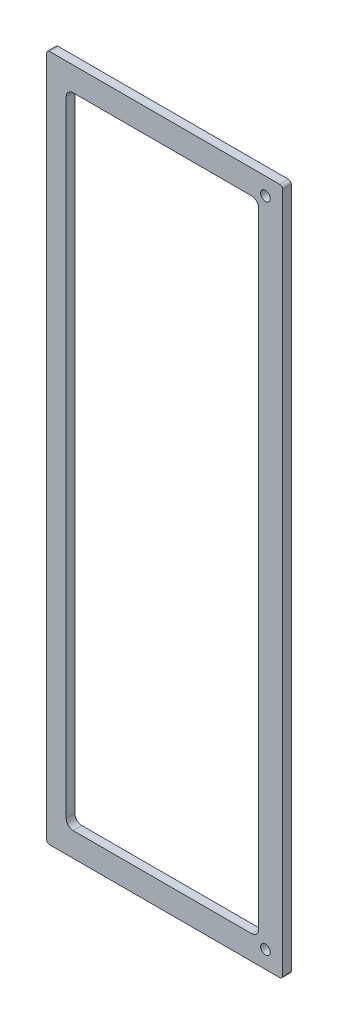
SolidWorks part; units mm, degrees
ref_plane "Front Plane" through (0, 0, 0) normal (1, 0, 0) x (0, 1, 0)
ref_plane "Top Plane" through (0, 0, 0) normal (0, 0, 1) x (0, 1, 0)
ref_plane "Right Plane" through (0, 0, 0) normal (0, 1, 0) x (-1, 0, 0)
sketch "Sketch1" plane through (0, 0, 0) normal (0, 0, 1) x (0, 1, 0)
  line L0 (12.5, 12.5) -> (12.5, 137.5)
  line L1 (-12.5, -12.5) -> (12.5, -12.5)
  line L2 (-12.5, -12.5) -> (-12.5, 12.5)
  line L3 (-12.5, 12.5) -> (12.5, 12.5)
  line L4 (12.5, -12.5) -> (12.5, 12.5)
  line L5 (-12.5, -12.5) -> (12.5, 12.5) construction
  line L6 (-12.5, 12.5) -> (12.5, -12.5) construction
  line L7 (-12.5, -12.5) -> (487.5, -12.5)
  line L8 (-12.5, -12.5) -> (-12.5, 162.5)
  line L9 (-12.5, 162.5) -> (487.5, 162.5)
  line L10 (487.5, -12.5) -> (487.5, 162.5)
  line L11 (-12.5, -12.5) -> (487.5, 162.5) construction
  line L12 (-12.5, 162.5) -> (487.5, -12.5) construction
  line L13 (487.5, -12.5) -> (462.5, -12.5)
  line L14 (487.5, -12.5) -> (487.5, 12.5)
  line L15 (487.5, 12.5) -> (462.5, 12.5)
  line L16 (462.5, -12.5) -> (462.5, 12.5)
  line L17 (487.5, -12.5) -> (462.5, 12.5) construction
  line L18 (487.5, 12.5) -> (462.5, -12.5) construction
  line L19 (-12.5, 162.5) -> (487.5, 162.5)
  line L20 (-12.5, 162.5) -> (-12.5, 137.5)
  line L21 (-12.5, 137.5) -> (487.5, 137.5)
  line L22 (487.5, 162.5) -> (487.5, 137.5)
  line L23 (-12.5, 162.5) -> (487.5, 137.5) construction
  line L24 (-12.5, 137.5) -> (487.5, 162.5) construction
  line L25 (12.5, 12.5) -> (462.5, 12.5)
  line L26 (462.5, 12.5) -> (462.5, 137.5)
  circle A0 centre (0, 0) radius 3.5
  circle A1 centre (475, 0) radius 3.5
  point P0 (0, 0)
  point P11 (237.5, 75)
  point P15 (475, 0)
  point P20 (237.5, 150)
  dimension "D2" = 7
  dimension "D6" = 7
  dimension "D1" = 25
  dimension "D3" = 500
  dimension "D4" = 175
  dimension "D5" = 25
  dimension "D7" = 25
extrude "Boss-Extrude1" add sketch "Sketch1" along normal blind 6.35 contours L8 L21 L10 L9 | L21 L8 L3 L0 | L25 L4 L7 L16 | L26 L15 L10 L21 | L16 L7 L10 L15 A1 | L1 L4 L3 L2 A0
sketch "Sketch2" plane through (0, 0, 6.35) normal (0, 0, 1) x (1, 0, 0)
  line L0 (-137.5, 12.5) -> (-12.5, 462.5) construction
  line L1 (12.5, -12.5) -> (-12.5, -12.5) construction
  line L2 (12.5, -12.5) -> (12.5, 12.5) construction
  line L3 (12.5, 12.5) -> (-12.5, 12.5) construction
  line L4 (-12.5, -12.5) -> (-12.5, 12.5) construction
  line L5 (12.5, -12.5) -> (-12.5, 12.5) construction
  line L6 (12.5, 12.5) -> (-12.5, -12.5) construction
  line L8 (-145, 470) -> (-5, 470)
  line L9 (-145, 470) -> (-145, 5)
  line L10 (-145, 5) -> (-5, 5)
  line L11 (-5, 470) -> (-5, 5)
  line L12 (-145, 470) -> (-5, 5) construction
  line L13 (-145, 5) -> (-5, 470) construction
  point P4 (0, 0)
  point P11 (-75, 237.5)
  dimension "D1" = 5
  dimension "D2" = 5
extrude "Cut-Extrude1" cut sketch "Sketch2" against normal through all
sketch "Sketch3" plane through (0, 0, 6.35) normal (0, 0, 1) x (1, 0, 0)
  line L0 (12.5, -12.5) -> (-162.5, -12.5) construction
  line L1 (-162.5, 487.5) -> (-159.25, 487.5)
  line L2 (-162.5, 487.5) -> (-162.5, -12.5)
  line L3 (-162.5, -12.5) -> (-159.25, -12.5)
  line L4 (-159.25, 487.5) -> (-159.25, -12.5)
  line L5 (-162.5, 487.5) -> (-159.25, -12.5) construction
  line L6 (-162.5, -12.5) -> (-159.25, 487.5) construction
  point P4 (-160.875, 237.5)
  dimension "D1" = 3.25
extrude "Cut-Extrude2" cut sketch "Sketch3" against normal through all
fillet "Fillet1" radius 2.13 4 edges at (-159.25, 487.5, 3.175) (12.5, 487.5, 3.175) (12.5, -12.5, 3.175) (-159.25, -12.5, 3.175)
fillet "Fillet2" radius 5 4 edges at (-5, 5, 3.175) (-145, 5, 3.175) (-145, 470, 3.175) (-5, 470, 3.175)
